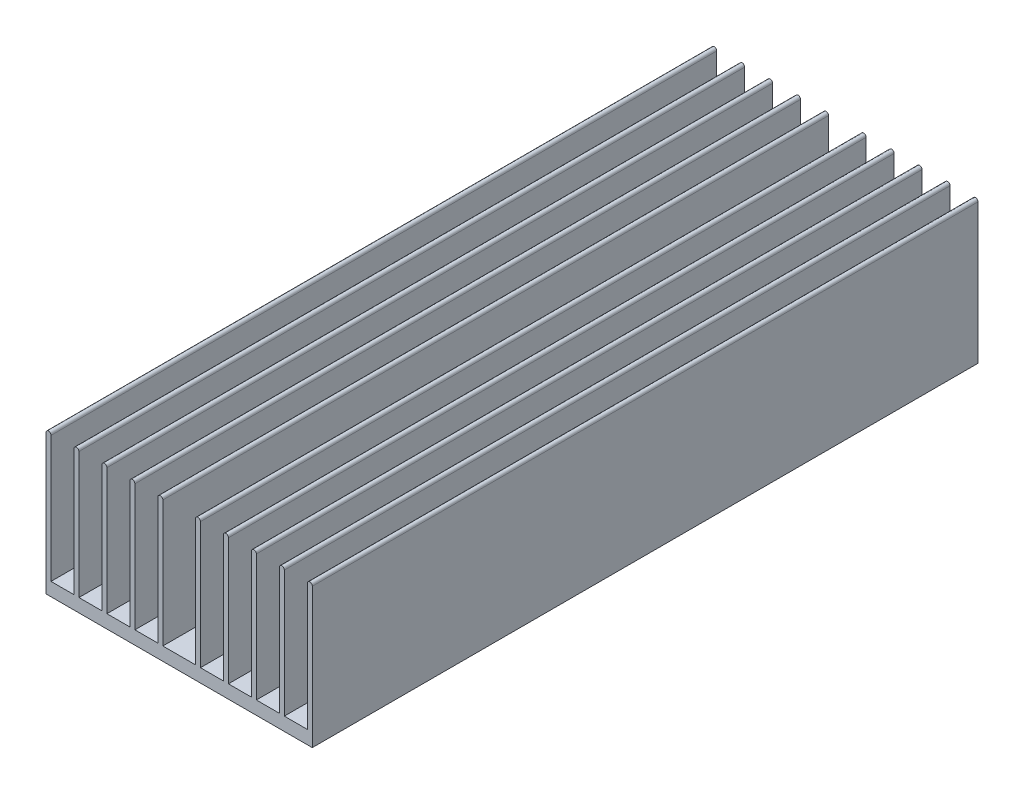
SolidWorks part; units mm, degrees
ref_plane "Alzado" through (0, 0, 0) normal (0, 0, 1) x (1, 0, 0)
ref_plane "Planta" through (0, 0, 0) normal (0, 1, 0) x (1, 0, 0)
ref_plane "Vista lateral" through (0, 0, 0) normal (1, 0, 0) x (0, 0, -1)
sketch "Croquis1" plane through (0, 0, 0) normal (0, 0, 1) x (1, 0, 0)
  line L0 (0, 0) -> (40, 0)
  line L1 (40, 0) -> (40, 42)
  line L2 (38.5, 42) -> (38.5, 4)
  line L5 (0, 0) -> (0, 38.4682) construction
  line L7 (31.6, 4) -> (38.5, 4)
  line L8 (31.6, 4) -> (31.6, 0)
  arc A0 (40, 42) -> (38.5, 42) centre (39.25, 42) ccw
  dimension "D1" = 42
  dimension "D3" = 4
  dimension "D4" = 1.5
  dimension "D6" = 40
  dimension "D2" = 8.4
extrude "Saliente-Extruir1" add sketch "Croquis1" along normal blind 200 contours L1 A0 L2 L7 L8 L0
pattern_linear "MatrizL1" count 5 spacing 8.4 along (-1, 0, 0) of "Saliente-Extruir1"
mirror "Simetría1" about plane through (0, 0, 0) normal (1, 0, 0) of "MatrizL1", "Saliente-Extruir1"
